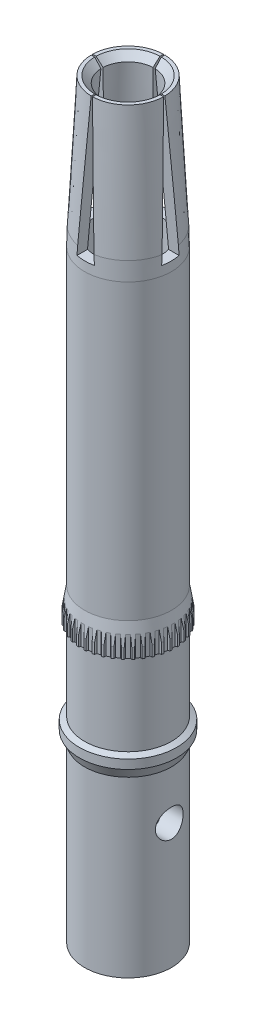
SolidWorks part; units mm, degrees
material "Phosphor bronze 10% D, UNS C52400"
ref_plane "Ön Düzlem" through (0, 0, 0) normal (0, 0, 1) x (1, 0, 0)
ref_plane "Üst Düzlem" through (0, 0, 0) normal (0, 1, 0) x (1, 0, 0)
ref_plane "Sağ Düzlem" through (0, 0, 0) normal (1, 0, 0) x (0, 0, -1)
sketch "Sketch1" plane through (0, 0, 0) normal (0, 0, 1) x (1, 0, 0)
  line L1 (-0.625, 0) -> (-0.35, 0)
  line L2 (-0.625, 0) -> (-0.625, 2.5)
  line L6 (-0.35, 0) -> (-0.35, 2.45)
  line L7 (-0.35, 2.45) -> (0, 2.45)
  line L9 (-0.625, 2.5) -> (-0.7, 2.65)
  line L10 (-0.7, 2.65) -> (-0.7, 2.78)
  line L11 (-0.7, 2.78) -> (-0.625, 2.8175)
  line L12 (-0.625, 2.8175) -> (-0.625, 4)
  line L13 (-0.625, 4) -> (-0.6739, 4)
  line L14 (-0.6739, 4) -> (-0.6739, 4.15)
  line L15 (-0.6739, 4.15) -> (-0.625, 4.45)
  line L16 (-0.625, 4.45) -> (-0.625, 8.6691)
  line L17 (0, 2.45) -> (0, 7.5146)
  line L18 (0, 7.5146) -> (-0.475, 7.8)
  line L19 (-0.475, 7.8) -> (-0.475, 8.8)
  line L20 (-0.625, 8.6691) -> (-0.6181, 8.9308)
  line L21 (-0.5202, 10.8) -> (-0.6181, 8.9308)
  line L22 (-0.5202, 10.8) -> (-0.47, 10.8)
  line L23 (-0.47, 10.8) -> (-0.375, 10.705)
  line L24 (-0.475, 8.8) -> (-0.375, 10.705)
  dimension "D1" = 0.35
  dimension "D2" = 0.625
  dimension "D3" = 2.45
  dimension "D4" = 2.5
  dimension "D5" = 0.7
  dimension "D6" = 2.65
  dimension "D7" = 2.78
  dimension "D8" = 4
  dimension "D9" = 0.6739
  dimension "D10" = 4.15
  dimension "D11" = 4.45
  dimension "D12" = 8.6691
  dimension "D13" = 7.5146
  dimension "D14" = 0.475
  dimension "D15" = 7.8
  dimension "D16" = 8.8
  dimension "D17" = 8.9308
  dimension "D18" = 0.6181
  dimension "D19" = 10.8
  dimension "D20" = 0.5202
  dimension "D21" = 0.47
  dimension "D22" = 0.375
  dimension "D23" = 10.705
ref_axis "Axis1" through (0, 0, 0) along (0, 1, 0)
revolve "Revolve1" add sketch "Sketch1" angle 360 about axis through (0, 0, 0) along (0, 1, 0)
sketch "Sketch3" plane through (0, 4, -4) normal (0, -1, 0) x (1, 0, 0)
  line L160 (0.6739, 3.9608) -> (0.6495, 3.9749)
  line L161 (0.6495, 4.0251) -> (0.6739, 4.0392)
  line L162 (0.6717, 4.0667) -> (0.6454, 4.0768)
  line L163 (0.6376, 4.1264) -> (0.6594, 4.1441)
  line L164 (0.653, 4.171) -> (0.6255, 4.1768)
  line L165 (0.61, 4.2246) -> (0.6288, 4.2455)
  line L166 (0.6182, 4.271) -> (0.5901, 4.2725)
  line L167 (0.5673, 4.3173) -> (0.5826, 4.3408)
  line L168 (0.5682, 4.3644) -> (0.5402, 4.3615)
  line L169 (0.5107, 4.4021) -> (0.5221, 4.4278)
  line L170 (0.5042, 4.4488) -> (0.477, 4.4415)
  line L171 (0.4415, 4.477) -> (0.4488, 4.5042)
  line L172 (0.4278, 4.5221) -> (0.4021, 4.5107)
  line L173 (0.3615, 4.5402) -> (0.3644, 4.5682)
  line L174 (0.3408, 4.5826) -> (0.3173, 4.5673)
  line L175 (0.2725, 4.5901) -> (0.271, 4.6182)
  line L176 (0.2455, 4.6288) -> (0.2246, 4.61)
  line L177 (0.1768, 4.6255) -> (0.171, 4.653)
  line L178 (0.1441, 4.6594) -> (0.1264, 4.6376)
  line L179 (0.0768, 4.6454) -> (0.0667, 4.6717)
  line L180 (0.0392, 4.6739) -> (0.0251, 4.6495)
  line L181 (-0.0251, 4.6495) -> (-0.0392, 4.6739)
  line L182 (-0.0667, 4.6717) -> (-0.0768, 4.6454)
  line L183 (-0.1264, 4.6376) -> (-0.1441, 4.6594)
  line L184 (-0.171, 4.653) -> (-0.1768, 4.6255)
  line L185 (-0.2246, 4.61) -> (-0.2455, 4.6288)
  line L186 (-0.271, 4.6182) -> (-0.2725, 4.5901)
  line L187 (-0.3173, 4.5673) -> (-0.3408, 4.5826)
  line L188 (-0.3644, 4.5682) -> (-0.3615, 4.5402)
  line L189 (-0.4021, 4.5107) -> (-0.4278, 4.5221)
  line L190 (-0.4488, 4.5042) -> (-0.4415, 4.477)
  line L191 (-0.477, 4.4415) -> (-0.5042, 4.4488)
  line L192 (-0.5221, 4.4278) -> (-0.5107, 4.4021)
  line L193 (-0.5402, 4.3615) -> (-0.5682, 4.3644)
  line L194 (-0.5826, 4.3408) -> (-0.5673, 4.3173)
  line L195 (-0.5901, 4.2725) -> (-0.6182, 4.271)
  line L196 (-0.6288, 4.2455) -> (-0.61, 4.2246)
  line L197 (-0.6255, 4.1768) -> (-0.653, 4.171)
  line L198 (-0.6594, 4.1441) -> (-0.6376, 4.1264)
  line L199 (-0.6454, 4.0768) -> (-0.6717, 4.0667)
  line L200 (-0.6739, 4.0392) -> (-0.6495, 4.0251)
  line L201 (-0.6495, 3.9749) -> (-0.6739, 3.9608)
  line L202 (-0.6717, 3.9333) -> (-0.6454, 3.9232)
  line L203 (-0.6376, 3.8736) -> (-0.6594, 3.8559)
  line L204 (-0.653, 3.829) -> (-0.6255, 3.8232)
  line L205 (-0.61, 3.7754) -> (-0.6288, 3.7545)
  line L206 (-0.6182, 3.729) -> (-0.5901, 3.7275)
  line L207 (-0.5673, 3.6827) -> (-0.5826, 3.6592)
  line L208 (-0.5682, 3.6356) -> (-0.5402, 3.6385)
  line L209 (-0.5107, 3.5979) -> (-0.5221, 3.5722)
  line L210 (-0.5042, 3.5512) -> (-0.477, 3.5585)
  line L211 (-0.4415, 3.523) -> (-0.4488, 3.4958)
  line L212 (-0.4278, 3.4779) -> (-0.4021, 3.4893)
  line L213 (-0.3615, 3.4598) -> (-0.3644, 3.4318)
  line L214 (-0.3408, 3.4174) -> (-0.3173, 3.4327)
  line L215 (-0.2725, 3.4099) -> (-0.271, 3.3818)
  line L216 (-0.2455, 3.3712) -> (-0.2246, 3.39)
  line L217 (-0.1768, 3.3745) -> (-0.171, 3.347)
  line L218 (-0.1441, 3.3406) -> (-0.1264, 3.3624)
  line L219 (-0.0768, 3.3546) -> (-0.0667, 3.3283)
  line L220 (-0.0392, 3.3261) -> (-0.0251, 3.3505)
  line L221 (0.0251, 3.3505) -> (0.0392, 3.3261)
  line L222 (0.0667, 3.3283) -> (0.0768, 3.3546)
  line L223 (0.1264, 3.3624) -> (0.1441, 3.3406)
  line L224 (0.171, 3.347) -> (0.1768, 3.3745)
  line L225 (0.2246, 3.39) -> (0.2455, 3.3712)
  line L226 (0.271, 3.3818) -> (0.2725, 3.4099)
  line L227 (0.3173, 3.4327) -> (0.3408, 3.4174)
  line L228 (0.3644, 3.4318) -> (0.3615, 3.4598)
  line L229 (0.4021, 3.4893) -> (0.4278, 3.4779)
  line L230 (0.4488, 3.4958) -> (0.4415, 3.523)
  line L231 (0.477, 3.5585) -> (0.5042, 3.5512)
  line L232 (0.5221, 3.5722) -> (0.5107, 3.5979)
  line L233 (0.5402, 3.6385) -> (0.5682, 3.6356)
  line L234 (0.5826, 3.6592) -> (0.5673, 3.6827)
  line L235 (0.5901, 3.7275) -> (0.6182, 3.729)
  line L236 (0.6288, 3.7545) -> (0.61, 3.7754)
  line L237 (0.6255, 3.8232) -> (0.653, 3.829)
  line L238 (0.6594, 3.8559) -> (0.6376, 3.8736)
  line L239 (0.6454, 3.9232) -> (0.6717, 3.9333)
  arc A160 (0.6495, 3.9749) -> (0.6495, 4.0251) centre (0, 4) ccw
  arc A161 (0.6739, 4.0392) -> (0.6717, 4.0667) centre (0, 4) ccw
  arc A162 (0.6454, 4.0768) -> (0.6376, 4.1264) centre (0, 4) ccw
  arc A163 (0.6594, 4.1441) -> (0.653, 4.171) centre (0, 4) ccw
  arc A164 (0.6255, 4.1768) -> (0.61, 4.2246) centre (0, 4) ccw
  arc A165 (0.6288, 4.2455) -> (0.6182, 4.271) centre (0, 4) ccw
  arc A166 (0.5901, 4.2725) -> (0.5673, 4.3173) centre (0, 4) ccw
  arc A167 (0.5826, 4.3408) -> (0.5682, 4.3644) centre (0, 4) ccw
  arc A168 (0.5402, 4.3615) -> (0.5107, 4.4021) centre (0, 4) ccw
  arc A169 (0.5221, 4.4278) -> (0.5042, 4.4488) centre (0, 4) ccw
  arc A170 (0.477, 4.4415) -> (0.4415, 4.477) centre (0, 4) ccw
  arc A171 (0.4488, 4.5042) -> (0.4278, 4.5221) centre (0, 4) ccw
  arc A172 (0.4021, 4.5107) -> (0.3615, 4.5402) centre (0, 4) ccw
  arc A173 (0.3644, 4.5682) -> (0.3408, 4.5826) centre (0, 4) ccw
  arc A174 (0.3173, 4.5673) -> (0.2725, 4.5901) centre (0, 4) ccw
  arc A175 (0.271, 4.6182) -> (0.2455, 4.6288) centre (0, 4) ccw
  arc A176 (0.2246, 4.61) -> (0.1768, 4.6255) centre (0, 4) ccw
  arc A177 (0.171, 4.653) -> (0.1441, 4.6594) centre (0, 4) ccw
  arc A178 (0.1264, 4.6376) -> (0.0768, 4.6454) centre (0, 4) ccw
  arc A179 (0.0667, 4.6717) -> (0.0392, 4.6739) centre (0, 4) ccw
  arc A180 (0.0251, 4.6495) -> (-0.0251, 4.6495) centre (0, 4) ccw
  arc A181 (-0.0392, 4.6739) -> (-0.0667, 4.6717) centre (0, 4) ccw
  arc A182 (-0.0768, 4.6454) -> (-0.1264, 4.6376) centre (0, 4) ccw
  arc A183 (-0.1441, 4.6594) -> (-0.171, 4.653) centre (0, 4) ccw
  arc A184 (-0.1768, 4.6255) -> (-0.2246, 4.61) centre (0, 4) ccw
  arc A185 (-0.2455, 4.6288) -> (-0.271, 4.6182) centre (0, 4) ccw
  arc A186 (-0.2725, 4.5901) -> (-0.3173, 4.5673) centre (0, 4) ccw
  arc A187 (-0.3408, 4.5826) -> (-0.3644, 4.5682) centre (0, 4) ccw
  arc A188 (-0.3615, 4.5402) -> (-0.4021, 4.5107) centre (0, 4) ccw
  arc A189 (-0.4278, 4.5221) -> (-0.4488, 4.5042) centre (0, 4) ccw
  arc A190 (-0.4415, 4.477) -> (-0.477, 4.4415) centre (0, 4) ccw
  arc A191 (-0.5042, 4.4488) -> (-0.5221, 4.4278) centre (0, 4) ccw
  arc A192 (-0.5107, 4.4021) -> (-0.5402, 4.3615) centre (0, 4) ccw
  arc A193 (-0.5682, 4.3644) -> (-0.5826, 4.3408) centre (0, 4) ccw
  arc A194 (-0.5673, 4.3173) -> (-0.5901, 4.2725) centre (0, 4) ccw
  arc A195 (-0.6182, 4.271) -> (-0.6288, 4.2455) centre (0, 4) ccw
  arc A196 (-0.61, 4.2246) -> (-0.6255, 4.1768) centre (0, 4) ccw
  arc A197 (-0.653, 4.171) -> (-0.6594, 4.1441) centre (0, 4) ccw
  arc A198 (-0.6376, 4.1264) -> (-0.6454, 4.0768) centre (0, 4) ccw
  arc A199 (-0.6717, 4.0667) -> (-0.6739, 4.0392) centre (0, 4) ccw
  arc A200 (-0.6495, 4.0251) -> (-0.6495, 3.9749) centre (0, 4) ccw
  arc A201 (-0.6739, 3.9608) -> (-0.6717, 3.9333) centre (0, 4) ccw
  arc A202 (-0.6454, 3.9232) -> (-0.6376, 3.8736) centre (0, 4) ccw
  arc A203 (-0.6594, 3.8559) -> (-0.653, 3.829) centre (0, 4) ccw
  arc A204 (-0.6255, 3.8232) -> (-0.61, 3.7754) centre (0, 4) ccw
  arc A205 (-0.6288, 3.7545) -> (-0.6182, 3.729) centre (0, 4) ccw
  arc A206 (-0.5901, 3.7275) -> (-0.5673, 3.6827) centre (0, 4) ccw
  arc A207 (-0.5826, 3.6592) -> (-0.5682, 3.6356) centre (0, 4) ccw
  arc A208 (-0.5402, 3.6385) -> (-0.5107, 3.5979) centre (0, 4) ccw
  arc A209 (-0.5221, 3.5722) -> (-0.5042, 3.5512) centre (0, 4) ccw
  arc A210 (-0.477, 3.5585) -> (-0.4415, 3.523) centre (0, 4) ccw
  arc A211 (-0.4488, 3.4958) -> (-0.4278, 3.4779) centre (0, 4) ccw
  arc A212 (-0.4021, 3.4893) -> (-0.3615, 3.4598) centre (0, 4) ccw
  arc A213 (-0.3644, 3.4318) -> (-0.3408, 3.4174) centre (0, 4) ccw
  arc A214 (-0.3173, 3.4327) -> (-0.2725, 3.4099) centre (0, 4) ccw
  arc A215 (-0.271, 3.3818) -> (-0.2455, 3.3712) centre (0, 4) ccw
  arc A216 (-0.2246, 3.39) -> (-0.1768, 3.3745) centre (0, 4) ccw
  arc A217 (-0.171, 3.347) -> (-0.1441, 3.3406) centre (0, 4) ccw
  arc A218 (-0.1264, 3.3624) -> (-0.0768, 3.3546) centre (0, 4) ccw
  arc A219 (-0.0667, 3.3283) -> (-0.0392, 3.3261) centre (0, 4) ccw
  arc A220 (-0.0251, 3.3505) -> (0.0251, 3.3505) centre (0, 4) ccw
  arc A221 (0.0392, 3.3261) -> (0.0667, 3.3283) centre (0, 4) ccw
  arc A222 (0.0768, 3.3546) -> (0.1264, 3.3624) centre (0, 4) ccw
  arc A223 (0.1441, 3.3406) -> (0.171, 3.347) centre (0, 4) ccw
  arc A224 (0.1768, 3.3745) -> (0.2246, 3.39) centre (0, 4) ccw
  arc A225 (0.2455, 3.3712) -> (0.271, 3.3818) centre (0, 4) ccw
  arc A226 (0.2725, 3.4099) -> (0.3173, 3.4327) centre (0, 4) ccw
  arc A227 (0.3408, 3.4174) -> (0.3644, 3.4318) centre (0, 4) ccw
  arc A228 (0.3615, 3.4598) -> (0.4021, 3.4893) centre (0, 4) ccw
  arc A229 (0.4278, 3.4779) -> (0.4488, 3.4958) centre (0, 4) ccw
  arc A230 (0.4415, 3.523) -> (0.477, 3.5585) centre (0, 4) ccw
  arc A231 (0.5042, 3.5512) -> (0.5221, 3.5722) centre (0, 4) ccw
  arc A232 (0.5107, 3.5979) -> (0.5402, 3.6385) centre (0, 4) ccw
  arc A233 (0.5682, 3.6356) -> (0.5826, 3.6592) centre (0, 4) ccw
  arc A234 (0.5673, 3.6827) -> (0.5901, 3.7275) centre (0, 4) ccw
  arc A235 (0.6182, 3.729) -> (0.6288, 3.7545) centre (0, 4) ccw
  arc A236 (0.61, 3.7754) -> (0.6255, 3.8232) centre (0, 4) ccw
  arc A237 (0.653, 3.829) -> (0.6594, 3.8559) centre (0, 4) ccw
  arc A238 (0.6376, 3.8736) -> (0.6454, 3.9232) centre (0, 4) ccw
  arc A239 (0.6717, 3.9333) -> (0.6739, 3.9608) centre (0, 4) ccw
extrude "Cut-Extrude1" cut sketch "Sketch3" against normal blind 1 flip side to cut
sketch "Sketch4" plane through (0, 0, 0) normal (0, 0, 1) x (1, 0, 0)
  line L0 (-0.01, 10.8) -> (-0.125, 8.8)
  line L1 (-0.125, 8.8) -> (0.125, 8.8)
  line L2 (0.125, 8.8) -> (0.01, 10.8)
  line L3 (0.01, 10.8) -> (-0.01, 10.8)
  line L4 (0, 8.8) -> (0, 10.8) construction
  line L5 (0, 0) -> (0, 0.3594) construction
  dimension "D1" = 0.25
  dimension "D2" = 0.02
  dimension "D3" = 2
  dimension "D4" = 10.8
extrude "Cut-Extrude2" cut sketch "Sketch4" against normal mid plane 2
pattern_circular "CirPattern1" count 2 every 90 about axis through (0, 10.8, 0) along (0, -1, 0) of "Cut-Extrude2"
sketch "Sketch5" plane through (0, 0, 0) normal (1, 0, 0) x (0, 0, -1)
  circle A0 centre (0, 1.8) radius 0.2
  dimension "D1" = 0.4
  dimension "D2" = 1.8
extrude "Cut-Extrude3" cut sketch "Sketch5" along normal blind 10
